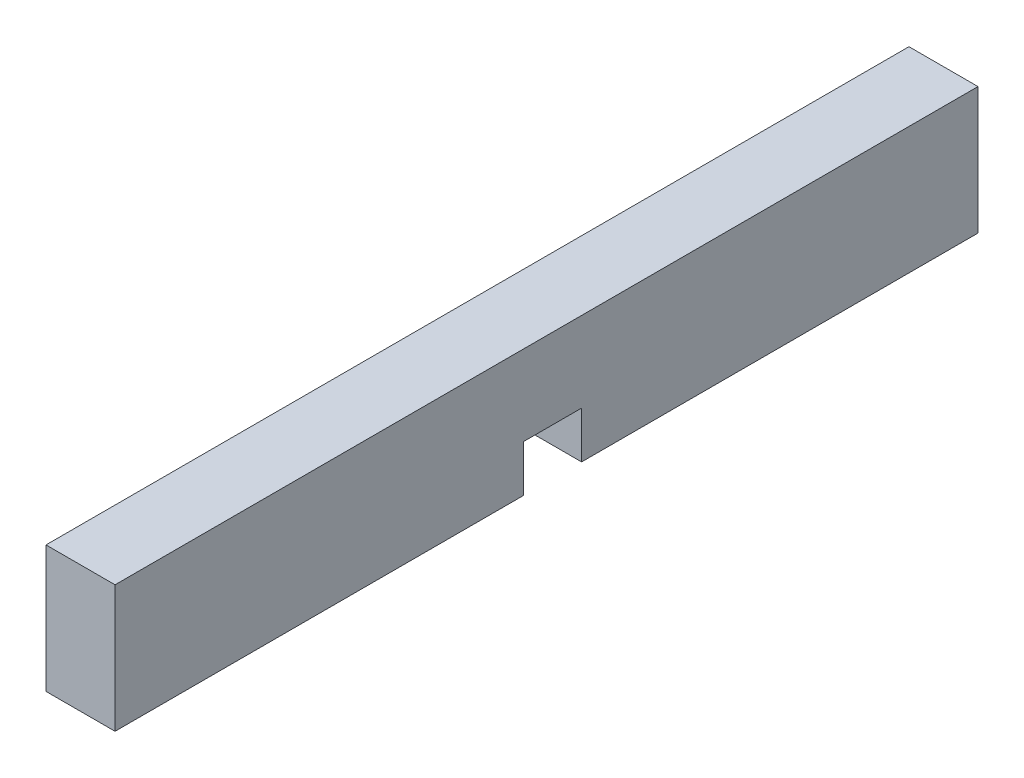
SolidWorks part; units mm, degrees
material "Chrome Stainless Steel"
ref_plane "Front Plane" through (0, 0, 0) normal (0, 0, 1) x (1, 0, 0)
ref_plane "Top Plane" through (0, 0, 0) normal (0, 1, 0) x (1, 0, 0)
ref_plane "Right Plane" through (0, 0, 0) normal (1, 0, 0) x (0, 0, -1)
sketch "Sketch2" plane through (0, 0, 0) normal (1, 0, 0) x (0, 0, -1)
  line L1 (-29.3624, 4.318) -> (29.3624, 4.318)
  line L2 (-29.3624, 4.318) -> (-29.3624, -4.318)
  line L3 (-29.3624, -4.318) -> (29.3624, -4.318)
  line L4 (29.3624, 4.318) -> (29.3624, -4.318)
  line L5 (-29.3624, 4.318) -> (29.3624, -4.318) construction
  line L6 (-29.3624, -4.318) -> (29.3624, 4.318) construction
  point P0 (0, 0)
  dimension "D1" = 58.7248
  dimension "D2" = 8.636
extrude "Boss-Extrude1" add sketch "Sketch2" along normal mid plane 4.699
sketch "Sketch3" plane through (2.3495, 0, 0) normal (1, 0, 0) x (0, 0, -1)
  line L0 (-29.3624, -4.318) -> (29.3624, -4.318) construction
  line L1 (-1.5748, -4.318) -> (2.3876, -4.318)
  line L2 (-1.5748, -4.318) -> (-1.5748, -1.143)
  line L3 (-1.5748, -1.143) -> (2.3876, -1.143)
  line L4 (2.3876, -4.318) -> (2.3876, -1.143)
  line L5 (-29.3624, 4.318) -> (-29.3624, -4.318) construction
  dimension "D1" = 27.7876
  dimension "D2" = 3.9624
  dimension "D3" = 3.175
extrude "Cut-Extrude1" cut sketch "Sketch3" against normal through all both and the other way through all
